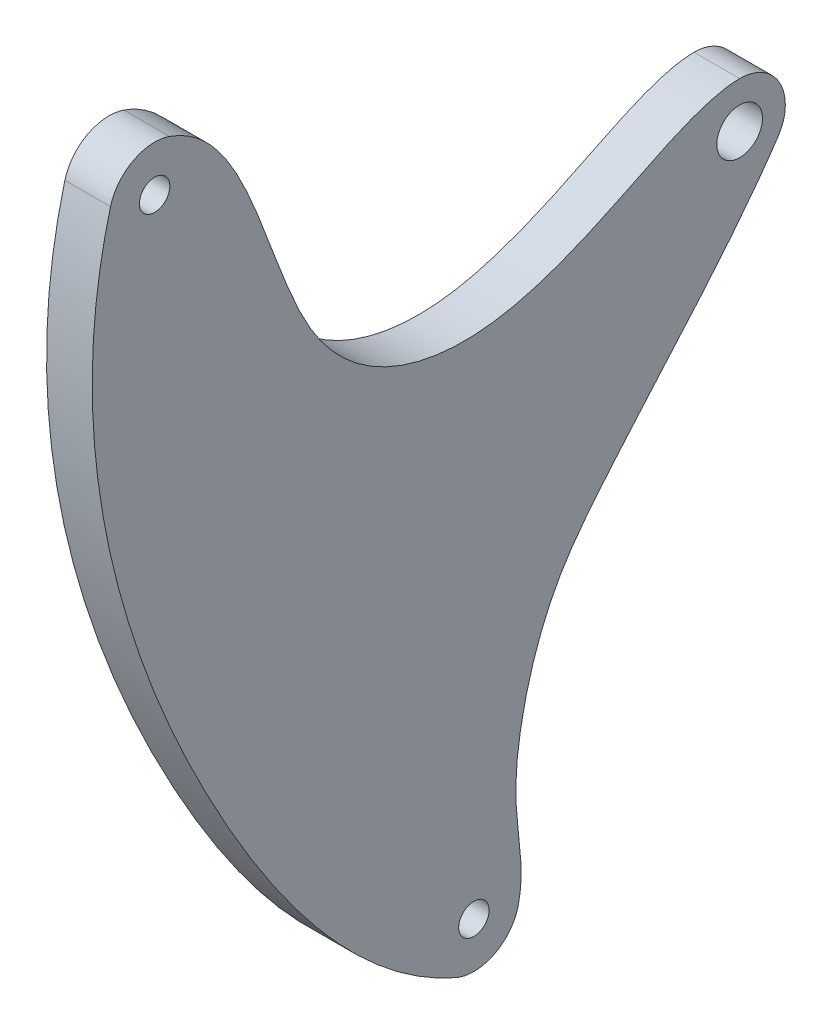
SolidWorks part; units mm, degrees
ref_plane "Front Plane" through (0, 0, 0) normal (1, 0, 0) x (0, 1, 0)
ref_plane "Top Plane" through (0, 0, 0) normal (0, 0, 1) x (0, 1, 0)
ref_plane "Right Plane" through (0, 0, 0) normal (0, 1, 0) x (-1, 0, 0)
sketch "Sketch1" plane through (0, 0, 0) normal (1, 0, 0) x (0, 1, 0)
  line L0 (34.9544, 81.6423) -> (174.7722, 81.6423) construction
  line L1 (65.8943, 10.0491) -> (83.7948, 55.6624) construction
  line L2 (83.7948, 55.6624) -> (52.1805, 74.3019) construction
  line L3 (52.1805, 74.3019) -> (65.8943, 10.0491) construction
  line L4 (83.7948, 55.6624) -> (128.0091, 98.9834) construction
  line L5 (128.0091, 98.9834) -> (90.89, 132.4822) construction
  line L6 (90.89, 132.4822) -> (75.2816, 94.0293) construction
  line L7 (75.2816, 94.0293) -> (83.7948, 55.6624) construction
  line L8 (52.1805, 74.3019) -> (39.1862, 111.4975) construction
  line L9 (39.1862, 111.4975) -> (90.89, 132.4822) construction
  line L10 (39.1862, 111.4975) -> (75.2816, 94.0293) construction
  line L11 (128.0091, 98.9834) -> (113.2816, 101.8293)
  dimension "D1" = 49
  dimension "D2" = 65.7
  dimension "D3" = 36.7
  dimension "D4" = 61.9
  dimension "D5" = 50
  dimension "D6" = 41.5
  dimension "D7" = 39.3
  dimension "D8" = 55.8
  dimension "D9" = 39.4
  dimension "D10" = 40.1
  dimension "D11" = 15
  dimension "D12" = 7.8
  dimension "D13" = 38
sketch "Sketch3" plane through (0, 0, 0) normal (1, 0, 0) x (0, 1, 0)
  circle A0 centre (52.1805, 74.3019) radius 10
  circle A2 centre (83.7948, 55.6624) radius 10
  circle A3 centre (128.0091, 98.9834) radius 10
  arc A6 (33.5834, 119.7805) -> (37.312, 101.6747) centre (39.1862, 111.4975) ccw
  arc A7 (99.4273, 127.2751) -> (89.1354, 142.3271) centre (90.89, 132.4822) ccw
  circle A14 centre (39.1862, 111.4975) radius 1
  circle A15 centre (90.89, 132.4822) radius 1
  circle A22 centre (75.2816, 94.0293) radius 1.375
  arc A25 (89.1354, 142.3271) -> (33.5834, 119.7805) centre (114.4647, 0.2089) ccw
  arc A30 (99.4273, 127.2751) -> (85.0328, 91.8129) centre (200.6568, 65.5324) ccw
  arc A32 (68.7412, 86.4647) -> (37.312, 101.6747) centre (24.6882, 35.5127) ccw
  arc A38 (68.7412, 86.4647) -> (85.0328, 91.8129) centre (75.2816, 94.0293) ccw
  arc A40 (29.2628, 112.7328) -> (24.2019, 112.8667) centre (24.6882, 35.5127) ccw construction
  dimension "D1" = 20
  dimension "D2" = 2
  dimension "D3" = 2
  dimension "D4" = 2.75
extrude "Boss-Extrude4" add sketch "Sketch3" along normal blind 3 contours A32 A38 A30 A7 A25 A6 A14 A15 A22
scale "Scale1" scale about centroid uniform scaling yes scale factor 2
sketch "Sketch4" plane through (4.5, 0, 0) normal (1, 0, 0) x (0, 1, 0)
  circle A0 centre (82.6858, 73.1032) radius 3
  dimension "D1" = 6
extrude "Cut-Extrude1" cut sketch "Sketch4" against normal through all
sketch "Sketch5" plane through (4.5, 0, 0) normal (1, 0, 0) x (0, 1, 0)
  arc A2 (130.9773, 139.5947) -> (102.1883, 68.6704) centre (333.4363, 16.1094) ccw construction
  arc A9 (119.5694, 148.0371) -> (115.4503, 155.806) centre (113.9027, 150.009) ccw
  arc A10 (81.4927, 67.223) -> (88.6858, 73.1032) centre (82.6858, 73.1032) ccw
  arc A11 (4.9948, 110.4368) -> (9.123, 102.1985) centre (10.4951, 108.0395) ccw
  spline S0 degree 3 poles (119.5694, 148.0371) (115.7779, 137.1414) (83.707, 134.2077) (74.3757, 110.4158) (80.753, 92.0886) (88.6858, 77.779) (88.6858, 73.1032) knots 0.022808 0.022808 0.022808 0.022808 0.378152 0.637109 0.823996 0.964332 0.964332 0.964332 0.964332
  spline S1 degree 3 poles (115.4503, 155.806) (92.2913, 161.9886) (50.145, 152.1958) (10.6403, 123.3898) (4.9948, 110.4368) knots 0.017812 0.017812 0.017812 0.017812 0.625021 0.983265 0.983265 0.983265 0.983265
  spline S2 degree 3 poles (9.123, 102.1985) (12.874, 101.3174) (20.3305, 103.1281) (32.4153, 101.6517) (43.0377, 97.937) (58.4382, 85.7864) (69.3867, 74.8535) (80.45, 67.4346) (81.4927, 67.223) knots 0 0 0 0 0.139373 0.261466 0.436165 0.534004 0.961982 1 1 1 1
  point P0 (90.0908, 113.5172)
  point P1 (113.7024, 105.3018)
  point P6 (9.123, 102.4818)
  point P8 (20.763, 102.4818)
  point P11 (30.9181, 101.527)
  point P13 (46.2621, 93.8336)
  point P14 (66.1353, 83.2425)
  point P15 (81.4927, 67.223)
  point P16 (51.1335, 91.4755)
  point P24 (44.5542, 96.3252)
  dimension "D1" = 25
  dimension "D3" = 12
  dimension "D4" = 12
  dimension "D5" = 12
extrude "Cut-Extrude2" cut sketch "Sketch5" against normal through all both and the other way through all flip side to cut
